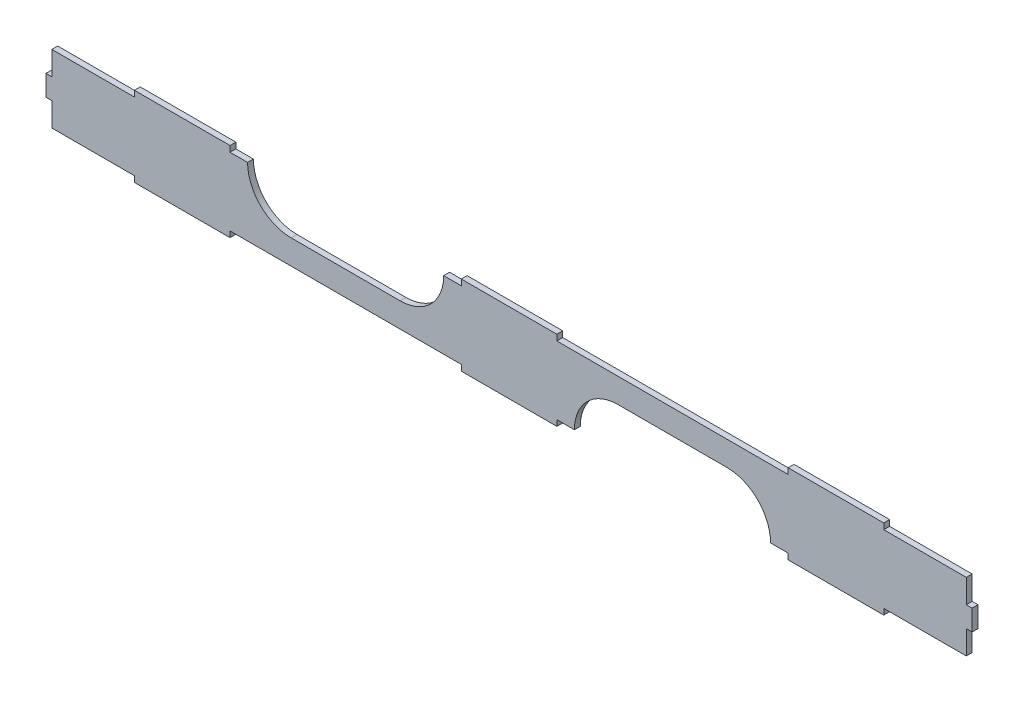
SolidWorks part; units mm, degrees
ref_plane "Front Plane" through (0, 0, 0) normal (0, 0, 1) x (1, 0, 0)
ref_plane "Top Plane" through (0, 0, 0) normal (0, 1, 0) x (1, 0, 0)
ref_plane "Right Plane" through (0, 0, 0) normal (1, 0, 0) x (0, 0, -1)
sketch "Sketch1" plane through (0, 0, 0) normal (0, 0, 1) x (1, 0, 0)
  line L0 (-335.7, 0) -> (335.7, 0) construction
  line L1 (-335.7, -25) -> (-275.1, -25)
  line L2 (-335.7, -25) -> (-335.7, -7.6)
  line L3 (-335.7, 25) -> (-275.1, 25)
  line L4 (335.7, -25) -> (335.7, -7.6)
  line L5 (-335.7, -25) -> (335.7, 25) construction
  line L6 (-335.7, 25) -> (335.7, -25) construction
  line L7 (0, -25) -> (0, 25) construction
  line L8 (35.1, -25) -> (48, -25)
  line L10 (-275.1, -25) -> (-275.1, -29.3)
  line L11 (-275.1, -29.3) -> (-204.9, -29.3)
  line L12 (-204.9, -25) -> (-204.9, -29.3)
  line L14 (-35.1, -25) -> (-35.1, -29.3)
  line L15 (-35.1, -29.3) -> (35.1, -29.3)
  line L16 (35.1, -25) -> (35.1, -29.3)
  line L18 (204.9, -25) -> (204.9, -29.3)
  line L19 (204.9, -29.3) -> (275.1, -29.3)
  line L20 (275.1, -25) -> (275.1, -29.3)
  line L21 (275.1, -25) -> (335.7, -25)
  line L22 (-204.9, -25) -> (-35.1, -25)
  line L23 (275.1, 25) -> (275.1, 29.3)
  line L24 (204.9, 29.3) -> (275.1, 29.3)
  line L25 (204.9, 25) -> (204.9, 29.3)
  line L26 (35.1, 25) -> (35.1, 29.3)
  line L27 (-35.1, 29.3) -> (35.1, 29.3)
  line L28 (-35.1, 25) -> (-35.1, 29.3)
  line L29 (-204.9, 25) -> (-204.9, 29.3)
  line L30 (-275.1, 29.3) -> (-204.9, 29.3)
  line L31 (-275.1, 25) -> (-275.1, 29.3)
  line L32 (-204.9, 25) -> (-192, 25)
  line L33 (35.1, 25) -> (204.9, 25)
  line L34 (275.1, 25) -> (335.7, 25)
  line L35 (-335.7, 7.6) -> (-335.7, 25)
  line L43 (335.7, 7.6) -> (335.7, 25)
  line L50 (-340, -7.6) -> (-335.7, -7.6)
  line L54 (-340, -7.6) -> (-340, 7.6)
  line L55 (-340, 7.6) -> (-335.7, 7.6)
  line L57 (-340, -7.6) -> (-335.7, 0) construction
  line L58 (-340, 7.6) -> (-335.7, 0) construction
  line L59 (335.7, -7.6) -> (340, -7.6)
  line L61 (335.7, 7.6) -> (340, 7.6)
  line L62 (340, -7.6) -> (340, 7.6)
  line L63 (335.7, 0) -> (340, 7.6) construction
  line L64 (335.7, 0) -> (340, -7.6) construction
  line L65 (80, 7) -> (160, 7)
  line L67 (192, -25) -> (204.9, -25)
  line L69 (-160, -7) -> (-80, -7)
  line L70 (-48, 25) -> (-35.1, 25)
  arc A0 (80, 7) -> (48, -25) centre (80, -25) ccw
  arc A1 (192, -25) -> (160, 7) centre (160, -25) ccw
  arc A2 (-192, 25) -> (-160, -7) centre (-160, 25) ccw
  arc A3 (-80, -7) -> (-48, 25) centre (-80, 25) ccw
  point P0 (0, 0)
  point P6 (335.7, 0)
  point P22 (0, -29.3)
  point P24 (240, -29.3)
  point P25 (-240, -29.3)
  point P38 (-120, -7)
  point P40 (-340, 0)
  point P43 (120, 7)
  point P47 (-335.7, 0)
  point P57 (-120, -25)
  point P62 (120, 25)
  dimension "D12" = 18
  dimension "D1" = 50
  dimension "D2" = 671.4
  dimension "D3" = 4.3
  dimension "D4" = 70.2
  dimension "D5" = 240
  dimension "D6" = 240
  dimension "D7" = 15.2
  dimension "D8" = 4.3
  dimension "D9" = 4.3
  dimension "D10" = 80
  dimension "D11" = 18
  dimension "D13" = 80
extrude "Boss-Extrude1" add sketch "Sketch1" along normal blind 4.3
